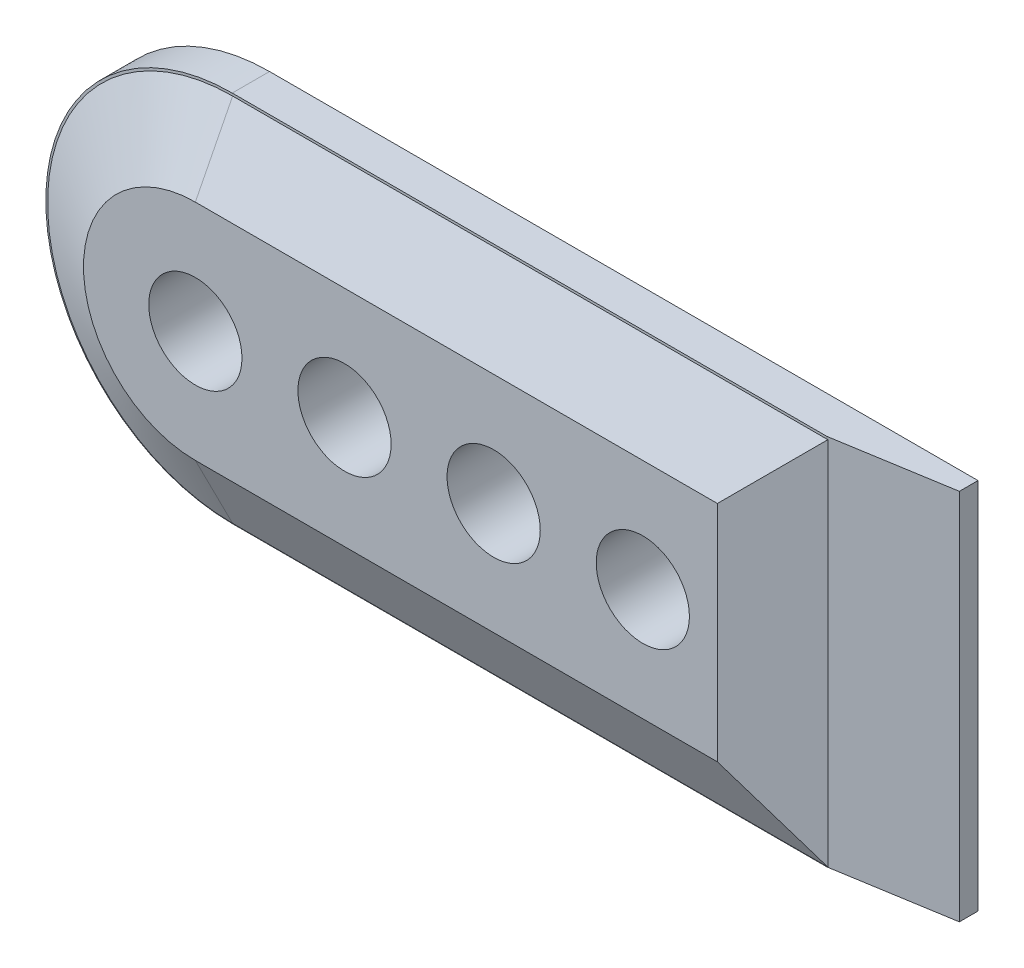
SolidWorks part; units mm, degrees
ref_plane "Front Plane" through (0, 0, 0) normal (0, 0, 1) x (1, 0, 0)
ref_plane "Top Plane" through (0, 0, 0) normal (0, 1, 0) x (1, 0, 0)
ref_plane "Right Plane" through (0, 0, 0) normal (1, 0, 0) x (0, 0, -1)
sketch "Sketch1" plane through (0, 0, 0) normal (0, 0, 1) x (1, 0, 0)
  line L1 (-68.6937, 19.0595) -> (51.9563, 19.0595)
  line L3 (-68.6937, -44.4405) -> (51.9563, -44.4405)
  line L4 (51.9563, 19.0595) -> (51.9563, -44.4405)
  arc A0 (-68.6937, 19.0595) -> (-68.6937, -44.4405) centre (-68.6937, -12.6905) ccw
  dimension "D1" = 120.65
  dimension "D2" = 63.5
extrude "Boss-Extrude1" add sketch "Sketch1" along normal blind 6.35 contours A0 L3 L4 L1
sketch3d "3DSketch1"
  line L0 (-68.6273, -31.9139, 12.7) -> (20.2727, -31.9139, 12.7)
  line L3 (-68.6273, 6.1861, 12.7) -> (20.2727, 6.1861, 12.7)
  line L4 (20.2727, -31.9139, 12.7) -> (20.2727, 6.1861, 12.7)
  arc A0 (-68.6273, 6.1861, 12.7) -> (-68.6273, -31.9139, 12.7) centre (-68.6273, -12.8639, 12.7) ccw
  point P0 (-68.6273, -12.8639, 12.7)
  point P3 (-68.6273, -12.8639, 31.75)
  dimension "D1" = 38.1
extrude "Boss-Extrude2" add sketch "3DSketch1" along direction (0, 0, 1) on the side against the normal up to surface (6.35 mm away) draft 63
sketch "Sketch3" plane through (0, -44.4405, 0) normal (0, -1, 0) x (1, 0, 0)
  line L0 (51.9563, 3.175) -> (32.5984, 6.35)
  line L1 (51.9563, 6.35) -> (51.9563, 0) construction
  line L2 (51.9563, 3.175) -> (51.9563, 0)
  line L3 (-68.6937, 6.35) -> (51.9563, 6.35) construction
  line L4 (32.5984, 6.35) -> (51.9563, 3.175)
  line M4 (51.9563, 0) -> (51.9563, 6.35)
  line M5 (51.9563, 6.35) -> (-68.6937, 6.35)
  dimension "D1" = 3.175
extrude "Cut-Extrude1" cut sketch "Sketch3" against normal blind 63.5 contours L0 M4 M5
sketch "Sketch4" plane through (0, 0, 12.7) normal (0, 0, 1) x (1, 0, 0)
  circle A1 centre (-68.6273, -12.8639) radius 7.9375
  circle A2 centre (-43.2273, -12.8639) radius 7.9375
  circle A3 centre (-17.8273, -12.8639) radius 7.9375
  circle A4 centre (7.5727, -12.8639) radius 7.9375
  dimension "D1" = 15.875
  dimension "D2" = 4
extrude "Cut-Extrude2" cut sketch "Sketch4" against normal blind 254 contours A1 | A2 | A3 | A4
